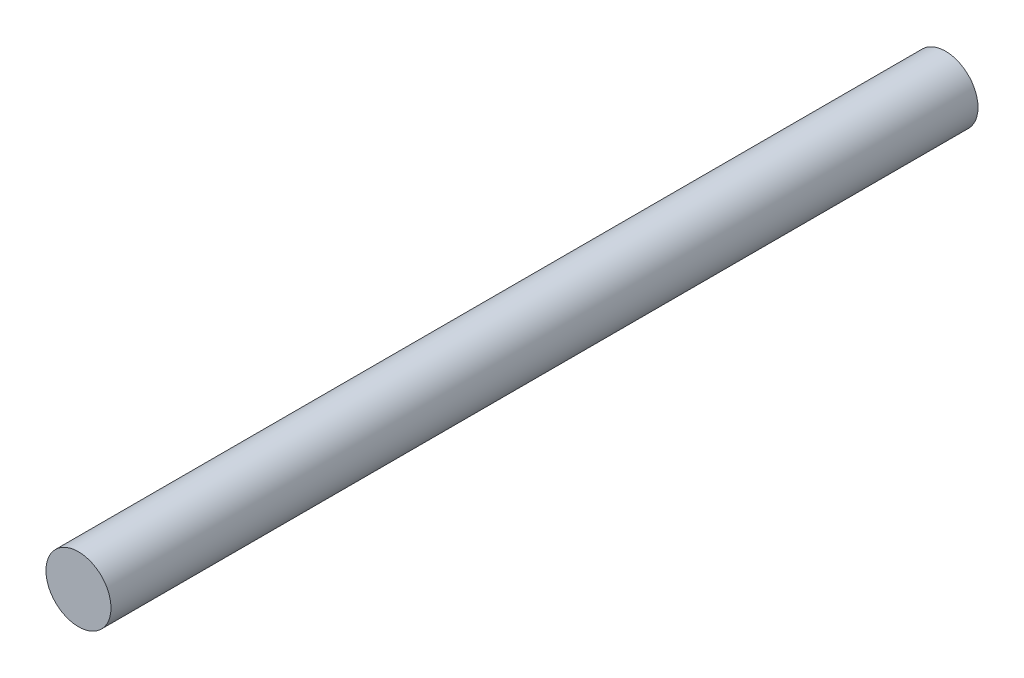
SolidWorks part; units mm, degrees
ref_plane "Plan de face" through (0, 0, 0) normal (0, 0, 1) x (1, 0, 0)
ref_plane "Plan de dessus" through (0, 0, 0) normal (0, 1, 0) x (1, 0, 0)
ref_plane "Plan de droite" through (0, 0, 0) normal (1, 0, 0) x (0, 0, -1)
sketch "Esquisse1" plane through (0, 0, 0) normal (0, 0, 1) x (1, 0, 0)
  circle A0 centre (0, 0) radius 3
  dimension "D1" = 6
extrude "Boss.-Extru.1" add sketch "Esquisse1" along normal blind 80
